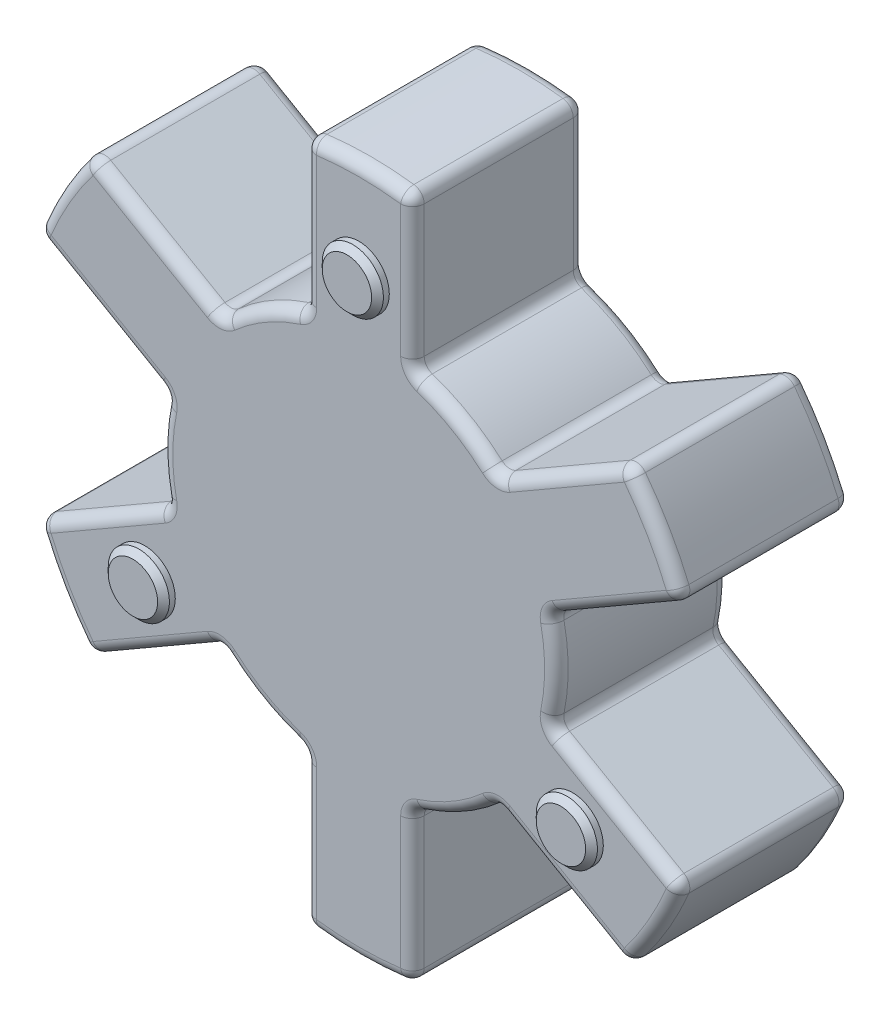
SolidWorks part; units mm, degrees
ref_plane "Front Plane" through (0, 0, 0) normal (0, 0, 1) x (1, 0, 0)
ref_plane "Top Plane" through (0, 0, 0) normal (0, 1, 0) x (1, 0, 0)
ref_plane "Right Plane" through (0, 0, 0) normal (1, 0, 0) x (0, 0, -1)
sketch "Sketch1" plane through (0, 0, 0) normal (0, 1, 0) x (1, 0, 0)
  line L0 (22.3647, 11.176) -> (0, 11.176)
  line L1 (0, 11.176) -> (0, 0)
  line L2 (0, 0) -> (22.3647, 0)
  line L3 (22.3647, 0) -> (22.3647, 11.176)
  line L4 (0, 11.176) -> (0, 0) construction
revolve "Revolve1" add sketch "Sketch1" angle 360 about L4
sketch "Sketch2" plane through (0, 0, -11.176) normal (0, 0, -1) x (-1, 0, 0)
  line L0 (3.4798, 22.0923) -> (3.4798, 12.3196)
  line L1 (8.9292, 9.1734) -> (17.3926, 14.0598)
  arc A0 (3.4798, 12.3196) -> (8.9292, 9.1734) centre (0, 0) cw
  arc A1 (17.3926, 14.0598) -> (3.4798, 22.0923) centre (0, 0) ccw
extrude "Cut-Extrude1" cut sketch "Sketch2" against normal through all
sketch "Sketch3" plane through (0, 0, -11.176) normal (0, 0, -1) x (-1, 0, 0)
  line L0 (20.8724, 8.0326) -> (12.409, 3.1462)
  line L1 (12.409, -3.1462) -> (20.8724, -8.0326)
  arc A0 (12.409, 3.1462) -> (12.409, -3.1462) centre (0, 0) cw
  arc A1 (20.8724, -8.0326) -> (20.8724, 8.0326) centre (0, 0) ccw
extrude "Cut-Extrude2" cut sketch "Sketch3" against normal through all
sketch "Sketch4" plane through (0, 0, -11.176) normal (0, 0, -1) x (-1, 0, 0)
  line L0 (17.3926, -14.0598) -> (8.9292, -9.1734)
  line L1 (3.4798, -12.3196) -> (3.4798, -22.0923)
  arc A0 (8.9292, -9.1734) -> (3.4798, -12.3196) centre (0, 0) cw
  arc A1 (3.4798, -22.0923) -> (17.3926, -14.0598) centre (0, 0) ccw
extrude "Cut-Extrude3" cut sketch "Sketch4" against normal through all
sketch "Sketch5" plane through (0, 0, -11.176) normal (0, 0, -1) x (-1, 0, 0)
  line L0 (-3.4798, -22.0923) -> (-3.4798, -12.3196)
  line L1 (-8.9292, -9.1734) -> (-17.3926, -14.0598)
  arc A0 (-3.4798, -12.3196) -> (-8.9292, -9.1734) centre (0, 0) cw
  arc A1 (-17.3926, -14.0598) -> (-3.4798, -22.0923) centre (0, 0) ccw
extrude "Cut-Extrude4" cut sketch "Sketch5" against normal through all
sketch "Sketch6" plane through (0, 0, -11.176) normal (0, 0, -1) x (-1, 0, 0)
  line L0 (-20.8724, -8.0326) -> (-12.409, -3.1462)
  line L1 (-12.409, 3.1462) -> (-20.8724, 8.0326)
  arc A0 (-12.409, -3.1462) -> (-12.409, 3.1462) centre (0, 0) cw
  arc A1 (-20.8724, 8.0326) -> (-20.8724, -8.0326) centre (0, 0) ccw
extrude "Cut-Extrude5" cut sketch "Sketch6" against normal through all
sketch "Sketch7" plane through (0, 0, -11.176) normal (0, 0, -1) x (-1, 0, 0)
  line L0 (-17.3926, 14.0598) -> (-8.9292, 9.1734)
  line L1 (-3.4798, 12.3196) -> (-3.4798, 22.0923)
  arc A0 (-8.9292, 9.1734) -> (-3.4798, 12.3196) centre (0, 0) cw
  arc A1 (-3.4798, 22.0923) -> (-17.3926, 14.0598) centre (0, 0) ccw
extrude "Cut-Extrude6" cut sketch "Sketch7" against normal through all
ref_plane "Plane1" through (0, -8.001, 0) normal (0, -1, 0) x (1, 0, 0)
sketch "Sketch8" plane through (0, -8.001, 0) normal (0, -1, 0) x (1, 0, 0)
  line L0 (15.8393, -11.176) -> (13.8581, -11.176)
  line L1 (13.8581, -11.176) -> (13.8581, -11.938)
  line L2 (13.8581, -11.938) -> (15.4583, -11.938)
  line L3 (15.4583, -11.938) -> (15.8393, -11.557)
  line L4 (15.8393, -11.557) -> (15.8393, -11.176)
  line L5 (13.8581, -11.176) -> (13.8581, -11.938) construction
revolve "Revolve2" add sketch "Sketch8" angle 360 about L5
sketch "Sketch9" plane through (0, -8.001, 0) normal (0, -1, 0) x (1, 0, 0)
  line L0 (-11.8769, -11.176) -> (-13.8581, -11.176)
  line L1 (-13.8581, -11.176) -> (-13.8581, -11.938)
  line L2 (-13.8581, -11.938) -> (-12.258, -11.938)
  line L3 (-12.258, -11.938) -> (-11.8769, -11.557)
  line L4 (-11.8769, -11.557) -> (-11.8769, -11.176)
  line L5 (-13.8581, -11.176) -> (-13.8581, -11.938) construction
revolve "Revolve3" add sketch "Sketch9" angle 360 about L5
ref_plane "Plane2" through (0, 16.002, 0) normal (0, -1, 0) x (1, 0, 0)
sketch "Sketch10" plane through (0, 16.002, 0) normal (0, -1, 0) x (1, 0, 0)
  line L0 (1.9812, -11.176) -> (0, -11.176)
  line L1 (0, -11.176) -> (0, -11.938)
  line L2 (0, -11.938) -> (1.6002, -11.938)
  line L3 (1.6002, -11.938) -> (1.9812, -11.557)
  line L4 (1.9812, -11.557) -> (1.9812, -11.176)
  line L5 (0, -11.176) -> (0, -11.938) construction
revolve "Revolve4" add sketch "Sketch10" angle 360 about L5
ref_plane "Plane3" through (0, -8.001, 0) normal (0, 1, 0) x (1, 0, 0)
sketch "Sketch11" plane through (0, -8.001, 0) normal (0, 1, 0) x (1, 0, 0)
  line L0 (15.8393, 0) -> (13.8581, 0)
  line L1 (13.8581, 0) -> (13.8581, -0.762)
  line L2 (13.8581, -0.762) -> (15.4583, -0.762)
  line L3 (15.4583, -0.762) -> (15.8393, -0.381)
  line L4 (15.8393, -0.381) -> (15.8393, 0)
  line L5 (13.8581, 0) -> (13.8581, -0.762) construction
revolve "Revolve5" add sketch "Sketch11" angle 360 about L5
sketch "Sketch12" plane through (0, -8.001, 0) normal (0, 1, 0) x (1, 0, 0)
  line L0 (-11.8769, 0) -> (-13.8581, 0)
  line L1 (-13.8581, 0) -> (-13.8581, -0.762)
  line L2 (-13.8581, -0.762) -> (-12.258, -0.762)
  line L3 (-12.258, -0.762) -> (-11.8769, -0.381)
  line L4 (-11.8769, -0.381) -> (-11.8769, 0)
  line L5 (-13.8581, 0) -> (-13.8581, -0.762) construction
revolve "Revolve6" add sketch "Sketch12" angle 360 about L5
ref_plane "Plane4" through (0, 16.002, 0) normal (0, 1, 0) x (1, 0, 0)
sketch "Sketch13" plane through (0, 16.002, 0) normal (0, 1, 0) x (1, 0, 0)
  line L0 (1.9812, 0) -> (0, 0)
  line L1 (0, 0) -> (0, -0.762)
  line L2 (0, -0.762) -> (1.6002, -0.762)
  line L3 (1.6002, -0.762) -> (1.9812, -0.381)
  line L4 (1.9812, -0.381) -> (1.9812, 0)
  line L5 (0, 0) -> (0, -0.762) construction
revolve "Revolve7" add sketch "Sketch13" angle 360 about L5
fillet "Fillet1" radius 0.762 72 edges at (13.1609, -11.6166, 0) (3.4798, -17.206, 0) (6.4008, -11.0865, 0) (3.4798, -12.3196, -5.588) (3.4798, -22.0923, -5.588) (3.4798, -17.206, -11.176) (13.1609, -11.6166, -11.176) (6.4008, -11.0865, -11.176) (17.3926, -14.0598, -5.588) (0, -22.3647, 0) (19.3684, -11.1824, 0) (0, -22.3647, -11.176) (-3.4798, -22.0923, -5.588) (19.3684, -11.1824, -11.176) (20.8724, -8.0326, -5.588) (-3.4798, -17.206, 0) (-3.4798, -12.3196, -5.588) (-13.1609, -11.6166, 0) (-6.4008, -11.0865, 0) (16.6407, -5.5894, 0) (12.8016, 0, 0) (16.6407, 5.5894, 0) (-3.4798, -17.206, -11.176) (-6.4008, -11.0865, -11.176) (-13.1609, -11.6166, -11.176) (-17.3926, -14.0598, -5.588) (16.6407, 5.5894, -11.176) (12.409, 3.1462, -5.588) (12.8016, 0, -11.176) (16.6407, -5.5894, -11.176) (20.8724, 8.0326, -5.588) (-19.3684, -11.1824, 0) (19.3684, 11.1824, 0) (-19.3684, -11.1824, -11.176) (-20.8724, -8.0326, -5.588) (19.3684, 11.1824, -11.176) (17.3926, 14.0598, -5.588) (-16.6407, -5.5894, 0) (-12.409, -3.1462, -5.588) (-16.6407, 5.5894, 0) (-12.8016, 0, 0) (-12.409, 3.1462, -5.588) (3.4798, 17.206, 0) (6.4008, 11.0865, 0) (13.1609, 11.6166, 0) (-16.6407, 5.5894, -11.176) (-16.6407, -5.5894, -11.176) (-12.8016, 0, -11.176) (-20.8724, 8.0326, -5.588) (13.1609, 11.6166, -11.176) (3.4798, 17.206, -11.176) (6.4008, 11.0865, -11.176) (3.4798, 12.3196, -5.588) (3.4798, 22.0923, -5.588) (-19.3684, 11.1824, 0) (0, 22.3647, 0) (-3.4798, 17.206, 0) (-6.4008, 11.0865, 0) (-13.1609, 11.6166, 0) (-19.3684, 11.1824, -11.176) (0, 22.3647, -11.176) (-17.3926, 14.0598, -5.588) (-3.4798, 22.0923, -5.588) (-13.1609, 11.6166, -11.176) (-6.4008, 11.0865, -11.176) (-3.4798, 17.206, -11.176) (-3.4798, 12.3196, -5.588) (-8.9292, 9.1734, -5.588) (12.409, -3.1462, -5.588) (-8.9292, -9.1734, -5.588) (8.9292, -9.1734, -5.588) (8.9292, 9.1734, -5.588)
